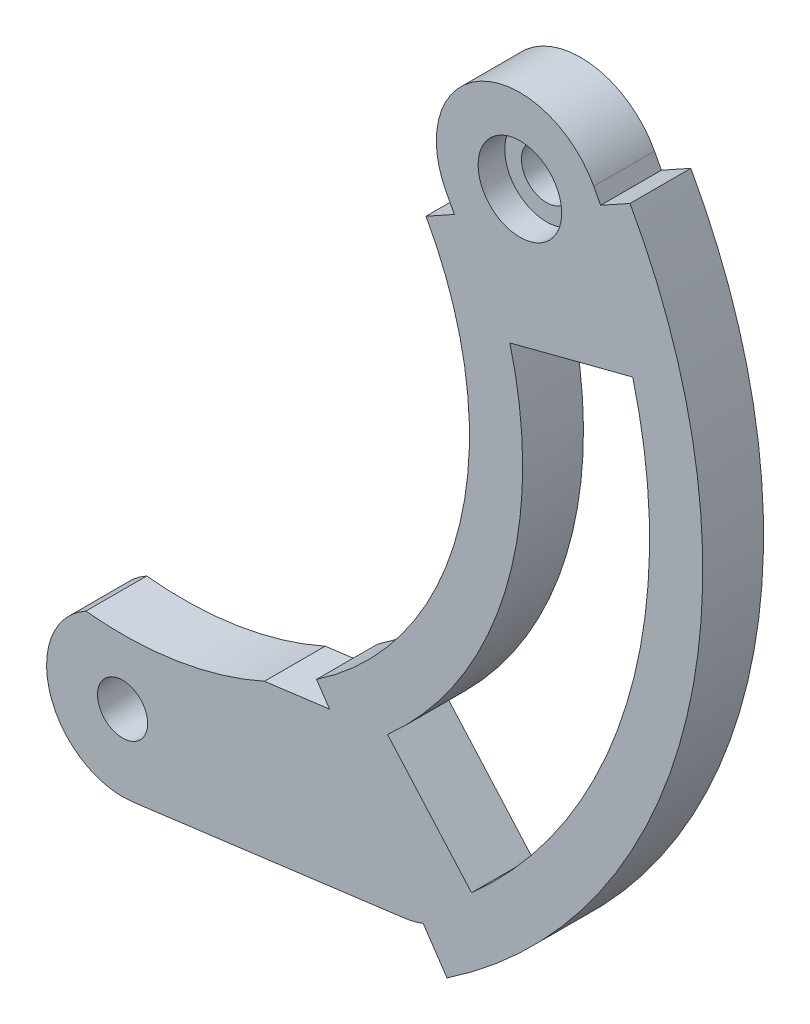
SolidWorks part; units mm, degrees
ref_plane "Front Plane" through (0, 0, 0) normal (0, 0, 1) x (1, 0, 0)
ref_plane "Top Plane" through (0, 0, 0) normal (0, 1, 0) x (1, 0, 0)
ref_plane "Right Plane" through (0, 0, 0) normal (1, 0, 0) x (0, 0, -1)
sketch "S01 - Eight millimetre track blank" plane through (0, 0, 0) normal (0, 0, 1) x (1, 0, 0)
  line L0 (25.5272, -37.8456) -> (42.6944, -63.297)
  line L1 (66.7772, 37.0152) -> (39.9264, 22.1316)
  arc A0 (42.6944, -63.297) -> (66.7772, 37.0152) centre (0, 0) ccw
  arc A1 (39.9264, 22.1316) -> (25.5272, -37.8456) centre (0, 0) cw
  dimension "D1" = 76.35
  dimension "D2" = 45.65
  dimension "D3" = 25.5272
  dimension "D4" = 39.9264
  dimension "D5" = 42.6944
  dimension "D6" = 66.7772
extrude "01 - Eight millimetre track blank" add sketch "S01 - Eight millimetre track blank" along normal blind 8
sketch "S02 - Lower cage tie landing" plane through (0, 0, 0) normal (0, 0, 1) x (1, 0, 0)
  line L0 (-1.2861, -44.083) -> (34.5688, -39.4331)
  line L1 (37.141, -59.267) -> (1.2861, -63.917)
  arc A0 (34.5688, -39.4331) -> (37.141, -59.267) centre (35.8549, -49.35) cw
  arc A1 (1.2861, -63.917) -> (-1.2861, -44.083) centre (0, -54) cw
  dimension "D1" = 10
  dimension "D2" = 10
  dimension "D3" = 1.2861
  dimension "D4" = 34.5688
  dimension "D5" = 35.8549
  dimension "D6" = 37.141
  dimension "D7" = 1.2861
  dimension "D8" = 39.4331
  dimension "D9" = 44.083
extrude "02 - Lower cage tie landing" add sketch "S02 - Lower cage tie landing" along normal blind 8
sketch "S03 - Bump end support landing" plane through (0, 0, 0) normal (0, 0, 1) x (1, 0, 0)
  line L0 (45.5724, 20.6155) -> (42.5748, 26.2531)
  line L1 (61.9996, 36.5815) -> (64.9972, 30.9439)
  arc A0 (42.5748, 26.2531) -> (61.9996, 36.5815) centre (52.2872, 31.4173) cw
  arc A1 (64.9972, 30.9439) -> (45.5724, 20.6155) centre (55.2848, 25.7797) cw
  dimension "D1" = 11
  dimension "D2" = 11
  dimension "D3" = 42.5748
  dimension "D4" = 45.5724
  dimension "D5" = 52.2872
  dimension "D6" = 55.2848
  dimension "D7" = 61.9996
  dimension "D8" = 64.9972
  dimension "D9" = 20.6155
  dimension "D10" = 26.2531
extrude "03 - Bump end support landing" add sketch "S03 - Bump end support landing" along normal blind 8
sketch "S04 - Relief for the swept floating guide barrels" plane through (0, 0, 0) normal (0, 0, 1) x (1, 0, 0)
  circle A0 centre (0, 0) radius 45.5
  dimension "D1" = 91
extrude "04 - Relief for the swept floating guide barrels" cut sketch "S04 - Relief for the swept floating guide barrels" along normal blind 8.2 from offset 0.1 offset against normal yes
sketch "S05 - Concentric guide and tangent stop faces" plane through (0, 0, 0) normal (0, 0, 1) x (1, 0, 0)
  line L0 (34.8622, -39.4544) -> (45.9201, -51.9689)
  line L1 (67.1301, 17.4059) -> (50.9647, 13.2145)
  arc A0 (45.9201, -51.9689) -> (67.1301, 17.4059) centre (0, 0) ccw
  arc A1 (50.9647, 13.2145) -> (34.8622, -39.4544) centre (0, 0) cw
  dimension "D1" = 69.35
  dimension "D2" = 52.65
  dimension "D3" = 34.8622
  dimension "D4" = 45.9201
  dimension "D5" = 50.9647
  dimension "D6" = 67.1301
extrude "05 - Concentric guide and tangent stop faces" cut sketch "S05 - Concentric guide and tangent stop faces" along normal blind 8.2 from offset 0.1 offset against normal yes
sketch "S06 - Support fasteners" plane through (0, 0, 0) normal (0, 0, 1) x (1, 0, 0)
  circle A0 centre (0, -54) radius 3.3
  circle A1 centre (52.2872, 31.4173) radius 3.3
  dimension "D1" = 6.6
  dimension "D2" = 6.6
  dimension "D3" = 52.2872
  dimension "D4" = 31.4173
  dimension "D5" = 54
extrude "06 - Support fasteners" cut sketch "S06 - Support fasteners" along normal blind 8.2 from offset 0.1 offset against normal yes
sketch "S07 - Bump end support register underside" plane through (0, 0, 0) normal (0, 0, 1) x (1, 0, 0)
  circle A0 centre (52.2872, 31.4173) radius 5.06
  dimension "D1" = 10.12
  dimension "D2" = 52.2872
  dimension "D3" = 31.4173
extrude "07 - Bump end support register underside" cut sketch "S07 - Bump end support register underside" along normal blind 1.35 from offset 0.1 offset against normal yes
sketch "S08 - Flush button screw counterbore outboard" plane through (0, 0, 0) normal (0, 0, 1) x (1, 0, 0)
  circle A0 centre (52.2872, 31.4173) radius 5.5
  dimension "D1" = 11
  dimension "D2" = 52.2872
  dimension "D3" = 31.4173
extrude "08 - Flush button screw counterbore outboard" cut sketch "S08 - Flush button screw counterbore outboard" along normal blind 3.6 from offset 4.5
sketch "S01 - Full diameter locating seat for printed post" plane through (0, 0, 0) normal (0, 0, 1) x (1, 0, 0)
  circle A0 centre (52.2872, 31.4173) radius 8.15
extrude "01 - Full diameter locating seat for printed post" cut sketch "S01 - Full diameter locating seat for printed post" along normal blind 1.35 from offset 0.1
